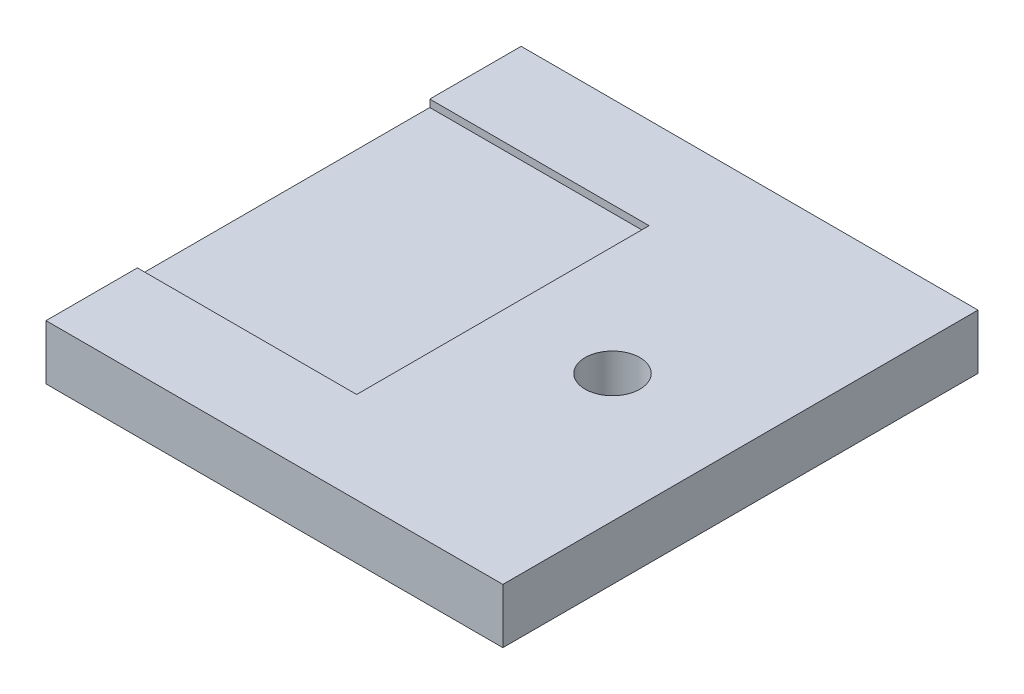
SolidWorks part; units mm, degrees
ref_plane "Front Plane" through (0, 0, 0) normal (0, 0, 1) x (1, 0, 0)
ref_plane "Top Plane" through (0, 0, 0) normal (0, 1, 0) x (1, 0, 0)
ref_plane "Right Plane" through (0, 0, 0) normal (1, 0, 0) x (0, 0, -1)
sketch "Sketch2" plane through (0, 0, 0) normal (0, 1, 0) x (1, 0, 0)
  line L1 (0, 0) -> (25, 0)
  line L2 (0, 0) -> (0, 26)
  line L3 (0, 26) -> (25, 26)
  line L4 (25, 0) -> (25, 26)
  circle A0 centre (18, 13) radius 1.5
  dimension "D3" = 3
  dimension "D1" = 25
  dimension "D2" = 26
  dimension "D4" = 18
  dimension "D5" = 13
extrude "Boss-Extrude1" add sketch "Sketch2" along normal blind 3
sketch "Sketch4" plane through (0, 3, 0) normal (0, 1, 0) x (1, 0, 0)
  line L0 (0, 26) -> (0, 0) construction
  line L1 (0, 21) -> (12, 21)
  line L2 (0, 21) -> (0, 5)
  line L3 (0, 5) -> (12, 5)
  line L4 (12, 21) -> (12, 5)
  line L5 (0, 0) -> (25, 0) construction
  line L6 (25, 26) -> (0, 26) construction
  dimension "D1" = 16
  dimension "D2" = 12
  dimension "D3" = 5
  dimension "D4" = 5
extrude "Cut-Extrude1" cut sketch "Sketch4" against normal blind 0.4
